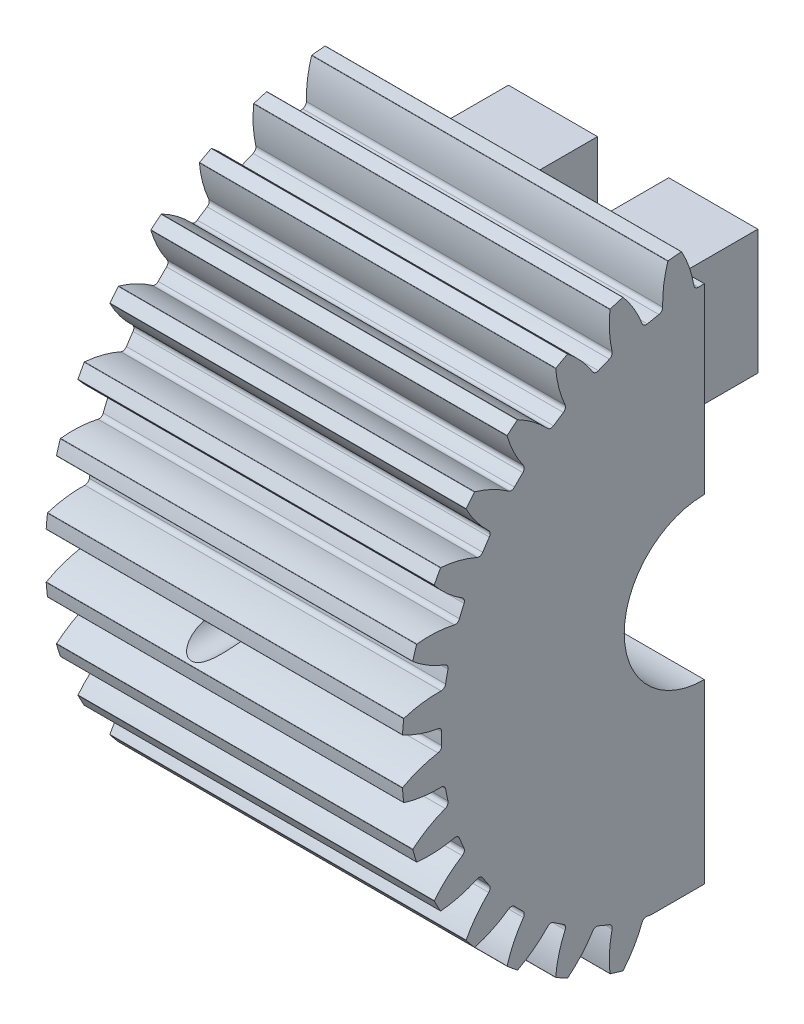
SolidWorks part; units mm, degrees
ref_plane "Plane1" through (0, 0, 0) normal (0, 0, 1) x (1, 0, 0)
ref_plane "Plane2" through (0, 0, 0) normal (0, 1, 0) x (1, 0, 0)
ref_plane "Plane3" through (0, 0, 0) normal (1, 0, 0) x (0, 0, -1)
other "Configuration Table"
sketch "HoldingSke" plane through (0, 0, 0) normal (0, 1, 0) x (1, 0, 0)
  line L0 (0, 0) -> (1.6961, -1.0598)
  line L1 (-15, 0) -> (100, 0) construction
  line L2 (0, 0) -> (-2.1039, 2.3779)
  line L3 (0, 0) -> (-11.863, 4.5341)
  line L4 (0, 0) -> (7.3237, 4.5764)
  line L5 (0, 0) -> (-46.8476, -17.4728)
  line L6 (0, 0) -> (-8.2896, -5.593)
  line L7 (-2.1039, 2.3779) -> (8.6586, 51.2059)
  line L8 (-76.2, 54.61) -> (-75.9, 54.61)
  line L9 (-67.7845, 28.3722) -> (-49.3413, 33.142)
  line L10 (-76.2, 71.12) -> (104.1128, 71.12)
  line L11 (0, 0) -> (-10, 0)
  line L12 (-76.2, 101.6) -> (-76.181, 101.6)
  line L13 (24.9733, 27.94) -> (52.9518, 28.4284)
  line L14 (24.9733, 27.94) -> (24.9743, 27.94)
  line L15 (24.9733, 27.94) -> (100.4006, 29.5858)
  line L16 (-63.627, -0.5) -> (-12.827, -0.5)
  circle A0 centre (0, 0) radius 1
  circle A1 centre (0, 0) radius 7.374
  circle A2 centre (0, 0) radius 37.5
  circle A3 centre (0, 0) radius 1
  dimension "MHD" = 14.748
  dimension "Hub_dia" = 75
  dimension "Bore" = 2
  dimension "MBD" = 2
  dimension "Num_teeth" = 32
  dimension "Pitch" = 2
  dimension "Overall_len" = 50
  dimension "Show_teeth" = 32
  dimension "Thickness" = 10
  dimension "OAL" = 50.0001
  dimension "T_dim" = 0.3
  dimension "Ap" = 14.5
  dimension "H" = 19.05
  dimension "Pitch_radius" = 180.3128
  dimension "Width" = 10
  dimension "Backlash" = 0.019
  dimension "Addendum_fac" = 1
  dimension "Dedendum_fac" = 1.25
  dimension "Clearance_fac" = 0.25
  dimension "Dedendum_add" = 0.001
  dimension "Module" = 0.5
sketch "BasProSke" plane through (0, 0, 0) normal (0, 1, 0) x (1, 0, 0)
  line L0 (-10, 0) -> (60, 0) construction
  line L1 (0, 0) -> (0, 8.5)
  line L2 (0, 0) -> (10, 0)
  line L3 (10, 0) -> (10, 8.5)
  line L4 (10, 8.5) -> (0, 8.5)
  dimension "Thickness" = 10
  dimension "Diameter" = 17
revolve "Base-Revolve" add sketch "BasProSke" angle 360 about L0
sketch "TooCutSke" plane through (0, 0, 0) normal (1, 0, 0) x (0, 0, -1)
  line L1 (0, 0) -> (0, 107) construction
  line L2 (0, 0) -> (-0.4258, 7.9887) construction
  line L3 (0, 0) -> (-1.5667, 15.9069) construction
  line L4 (-0.4258, 7.9887) -> (-0.7833, 7.9534) construction
  arc A0 (0.277, 7.3688) -> (-0.277, 7.3688) centre (0, 0) ccw
  arc A1 (0.6561, 8.5001) -> (-0.6561, 8.5001) centre (0, 0) ccw
  circle A2 centre (0, 0) radius 8 construction
  circle A3 centre (0, 0) radius 7.7452 construction
  arc A4 (-0.277, 7.3688) -> (-0.6561, 8.5001) centre (-3.4475, 6.9356) ccw
  arc A5 (0.6561, 8.5001) -> (0.277, 7.3688) centre (3.4475, 6.9356) ccw
  dimension "Root_dia" = 14.748
  dimension "Overcut_dia" = 17.0508
  dimension "Pitch_dia" = 16
  dimension "Base_dia" = 15.4904
  dimension "Flank_rad" = 3.2
  dimension "Half_ang" = 5.625
  dimension "Half_CT" = 0.3593
extrude "ToothCut" cut sketch "TooCutSke" along normal through all
fillet "Breaks" radius 0.01 2 edges at (5, 8.4757, -0.6425) (5, 8.4757, 0.6425)
fillet "RootFillets" radius 0.126 2 edges at (5, 7.3688, -0.277) (5, 7.3688, 0.277)
pattern_circular "TeethCuts" count 32 over 360 about axis through (0, 0, 0) along (1, 0, 0) of "ToothCut", "RootFillets", "Breaks"
sketch "HubNeaOneSke" plane through (0, 0, 0) normal (-1, 0, 0) x (0, 0, 1)
  circle A0 centre (0, 0) radius 7.374
  dimension "Diameter" = 14.748
extrude "HubNearOne" [suppressed] add sketch "HubNeaOneSke" along normal blind 40.0001
sketch "HubNeaBotSke" plane through (0, 0, 0) normal (-1, 0, 0) x (0, 0, 1)
  circle A0 centre (0, 0) radius 7.374
  dimension "Diameter" = 14.748
extrude "HubNearBoth" [suppressed] add sketch "HubNeaBotSke" along normal blind 20
ref_plane "FarPln" through (10, 0, 0) normal (1, 0, 0) x (0, 0, -1)
sketch "HubFarSke" plane through (10, 0, 0) normal (1, 0, 0) x (0, 0, -1)
  circle A0 centre (0, 0) radius 7.374
  dimension "Diameter" = 14.748
extrude "HubFar" [suppressed] add sketch "HubFarSke" along normal blind 20
sketch "BorSke" plane through (0, 0, 0) normal (1, 0, 0) x (0, 0, -1)
  circle A0 centre (0, 0) radius 1
  dimension "Diameter" = 2
extrude "Bore" cut sketch "BorSke" along normal mid plane 100.0001
sketch "KeySke" plane through (0, 0, 0) normal (1, 0, 0) x (0, 0, -1)
  line L0 (-0.4, 0) -> (-0.4, 1.3)
  line L1 (-0.4, 1.3) -> (0.4, 1.3)
  line L2 (0.4, 1.3) -> (0.4, 0)
  line L3 (0, 0) -> (0, 34) construction
  line L4 (-0.4, 0) -> (0.4, 0)
  dimension "Offset" = 1.3
  dimension "Width" = 0.8
extrude "Keyway" [suppressed] cut sketch "KeySke" along normal mid plane 100.0001
pattern_circular "Keyway2" [suppressed] count 2 every 90 about axis through (-10, 0, 0) along (1, 0, 0)
sketch "Sketch2" plane through (0, 0, 0) normal (-1, 0, 0) x (0, 0, 1)
  line L1 (-1.5, 0) -> (1.5, 0)
  line L2 (-1.5, 0) -> (-1.5, -10)
  line L3 (-1.5, -10) -> (1.5, -10)
  line L4 (1.5, 0) -> (1.5, -10)
  circle A0 centre (0, 0) radius 1 construction
  dimension "D3" = 1.5
  dimension "D1" = 10
  dimension "D2" = 3
  dimension "D4" = 0
extrude "Cut-Extrude2" cut sketch "Sketch2" against normal through all
sketch "Sketch3" plane through (0, 0, -1.5) normal (0, 0, 1) x (1, 0, 0)
  line L0 (0, 0.1666) -> (0, -0.1666) construction
  circle A0 centre (4, 0) radius 0.6
  dimension "D1" = 4
extrude "Cut-Extrude3" cut sketch "Sketch3" against normal through all both and the other way through all
sketch "Sketch4" plane through (0, 0, 0) normal (-1, 0, 0) x (0, 0, 1)
  circle A0 centre (0, 0) radius 1.5
  dimension "D1" = 3
extrude "Cut-Extrude4" cut sketch "Sketch4" against normal blind 6.5
sketch "Sketch7" plane through (0, 0, 0) normal (0, 0, 1) x (1, 0, 0)
  line L0 (4, 0) -> (4, 2.75)
  line L1 (4, 0) -> (4, -2.75)
  arc A0 (4, 2.75) -> (4, -2.75) centre (4, 0) ccw
  dimension "D1" = 2.75
  dimension "D2" = 2.75
revolve "Cut-Revolve1" cut sketch "Sketch7" angle 360 about L0
sketch "Sketch8" plane through (0, 0, 0) normal (0, 0, 1) x (1, 0, 0)
  line L0 (0, 0.1666) -> (0, -0.1666) construction
  line L1 (-0.5, 9) -> (10.5, 9)
  line L2 (-0.5, 9) -> (-0.5, -9)
  line L3 (-0.5, -9) -> (10.5, -9)
  line L4 (10.5, 9) -> (10.5, -9)
  point P7 (0, 0)
  dimension "D1" = 18
  dimension "D2" = 11
  dimension "D3" = 9
  dimension "D4" = 10.5
extrude "Cut-Extrude5" cut sketch "Sketch8" against normal blind 10
sketch "Sketch9" plane through (0, 0, 0) normal (0, 0, -1) x (-1, 0, 0)
  line L1 (-4, 6.45) -> (-1.5, 6.45)
  line L2 (-4, 6.45) -> (-4, 2.95)
  line L3 (-4, 2.95) -> (-1.5, 2.95)
  line L4 (-1.5, 6.45) -> (-1.5, 2.95)
  line L5 (-4, 6.45) -> (-1.5, 2.95) construction
  line L6 (-4, 2.95) -> (-1.5, 6.45) construction
  line L7 (-8.5, 6.45) -> (-6, 6.45)
  line L8 (-8.5, 6.45) -> (-8.5, 2.95)
  line L9 (-8.5, 2.95) -> (-6, 2.95)
  line L10 (-6, 6.45) -> (-6, 2.95)
  line L11 (-8.5, 6.45) -> (-6, 2.95) construction
  line L12 (-8.5, 2.95) -> (-6, 6.45) construction
  point P0 (-2.75, 4.7)
  point P5 (-7.25, 4.7)
  dimension "D1" = 3.5
  dimension "D2" = 3.5
  dimension "D3" = 2.5
  dimension "D4" = 2.5
  dimension "D5" = 4.7
  dimension "D6" = 4.7
  dimension "D7" = 8.5
  dimension "D8" = 4
extrude "Boss-Extrude1" add sketch "Sketch9" along normal blind 3
sketch "Sketch12" plane through (0, 0, 1.5) normal (0, 0, -1) x (-1, 0, 0)
  line L0 (-10, -7.2198) -> (0, -7.2198) construction
  line L1 (-10, 0) -> (-6.75, 0)
  line L2 (-10, 0) -> (-10, -7.2198)
  line L3 (-10, -7.2198) -> (-6.75, -7.2198)
  line L4 (-6.75, 0) -> (-6.75, -7.2198)
  dimension "D1" = 3.25
extrude "Boss-Extrude3" add sketch "Sketch12" along normal blind 1.5
sketch "Sketch1" plane through (10, 0, 0) normal (1, 0, 0) x (0, 0, -1)
  circle A0 centre (0, 0) radius 2.25
  dimension "D1" = 4.5
extrude "Cut-Extrude6" cut sketch "Sketch1" against normal blind 3.25
equation "' \"Module@HoldingSke\" = 6.35"
equation "' \"Num_teeth@HoldingSke\" = 12"
equation "' \"Ap@HoldingSke\" =  20"
equation "' \"Ap@HoldingSke\" = 20"
equation "' \"Width@HoldingSke\" = 0.5 * 25.4"
equation "' \"Hub_dia@HoldingSke\"= 1 * 25.4"
equation "' \"Hub_dia@HoldingSke\" = 1 * 25.4"
equation "' \"Overall_len@HoldingSke\" = 1.0 * 25.4"
equation "' \"Bore@HoldingSke\" = 0.75 * 25.4"
equation "' \"T_dim@HoldingSke\" = 0.1 * 25.4"
equation "' \"Width@KeySke\" = 0.25 * 25.4"
equation "' \"Show_teeth@HoldingSke\" = 13"
equation "' \"Backlash@HoldingSke\" = 0.009 * 25.4"
equation "' \"Addendum_fac@HoldingSke\" = 1.0"
equation "' \"Dedendum_fac@HoldingSke\" = 1.25"
equation "' \"Dedendum_add@HoldingSke\" = 0.00005 * 25.4"
equation "' \"Clearance_fac@HoldingSke\" = 0.25"
equation "\"Pitch@HoldingSke\" = 1 / \"Module@HoldingSke\""
equation "\"Overcut_dia@TooCutSke\" = (\"Num_teeth@HoldingSke\" + 2 * \"Addendum_fac@HoldingSke\") / \"Pitch@HoldingSke\" + 0.002 * 25.4"
equation "\"Pitch_dia@TooCutSke\" = \"Num_teeth@HoldingSke\" / \"Pitch@HoldingSke\""
equation "\"Base_dia@TooCutSke\" = \"Num_teeth@HoldingSke\" / \"Pitch@HoldingSke\" * cos((\"Ap@HoldingSke\"  * 3.14159265 / 180))"
equation "\"Root_dia@TooCutSke\" = (\"Num_teeth@HoldingSke\" + 2) / \"Pitch@HoldingSke\" - 2 * (\"Addendum_fac@HoldingSke\" + \"Dedendum_fac@HoldingSke\") / \"Pitch@HoldingSke\" - \"Dedendum_add@HoldingSke\" * 2"
equation "\"Half_ang@TooCutSke\" = 180 / \"Num_teeth@HoldingSke\""
equation "\"Half_CT@TooCutSke\" = \"Num_teeth@HoldingSke\" / \"Pitch@HoldingSke\" * sin((3.14159265 / 2 / \"Num_teeth@HoldingSke\")) / 2 - 7 * \"Backlash@HoldingSke\" / 4"
equation "\"Flank_rad@TooCutSke\" = \"Num_teeth@HoldingSke\" / \"Pitch@HoldingSke\" / 5"
equation "\"Radius@RootFillets\" = \"Clearance_fac@HoldingSke\" / \"Pitch@HoldingSke\" + \"Dedendum_add@HoldingSke\""
equation "\"Break_rad@Breaks\" = 0.02 / \"Pitch@HoldingSke\""
equation "\"Thickness@HoldingSke\" = \"Width@HoldingSke\""
equation "\"OAL@HoldingSke\" = \"Thickness@HoldingSke\""
equation "\"MHD@HoldingSke\" = (\"Num_teeth@HoldingSke\" + 2) / \"Pitch@HoldingSke\" - 2 * (\"Addendum_fac@HoldingSke\" + \"Dedendum_fac@HoldingSke\")  / \"Pitch@HoldingSke\" - \"Dedendum_add@HoldingSke\" * 2"
equation "\"MBD@HoldingSke\" = (\"Num_teeth@HoldingSke\" + 2) / \"Pitch@HoldingSke\" - 2 * (\"Addendum_fac@HoldingSke\" + \"Dedendum_fac@HoldingSke\")  / \"Pitch@HoldingSke\" - \"Dedendum_add@HoldingSke\" * 2 - 0.002 * 25.4"
equation "\"MHD@HoldingSke\" = ((sgn( \"MHD@HoldingSke\" - \"Hub_dia@HoldingSke\" )-1)*( \"MHD@HoldingSke\" - \"Hub_dia@HoldingSke\" ))/-2+ \"Hub_dia@HoldingSke\""
equation "\"MBD@HoldingSke\" = ((sgn( \"MBD@HoldingSke\" - \"Bore@HoldingSke\" )-1)*( \"MBD@HoldingSke\" - \"Bore@HoldingSke\" ))/-2+ \"Bore@HoldingSke\""
equation "\"OAL@HoldingSke\" = ((sgn( \"OAL@HoldingSke\" - \"Overall_len@HoldingSke\" )+1)*( \"OAL@HoldingSke\" - \"Overall_len@HoldingSke\" ))/2 + \"Overall_len@HoldingSke\" + 0.000002 * 25.4"
equation "\"Num_teeth@TeethCuts\" = int( \"Show_teeth@HoldingSke\" ) + 1"
equation "\"Num_teeth@TeethCuts\" = ((sgn( \"Num_teeth@TeethCuts\" - \"Num_teeth@HoldingSke\" )-1)*( \"Num_teeth@TeethCuts\" - \"Num_teeth@HoldingSke\" ))/-2+ \"Num_teeth@HoldingSke\""
equation "\"Num_teeth@TeethCuts\" = ((sgn( \"Num_teeth@TeethCuts\" - 2.0)+1)*( \"Num_teeth@TeethCuts\" - 2.0))/2 +2.0"
equation "\"Angle@TeethCuts\" = 360.0 / \"Num_teeth@HoldingSke\""
equation "\"Diameter@BasProSke\" = (\"Num_teeth@HoldingSke\" + 2 * \"Addendum_fac@HoldingSke\") / \"Pitch@HoldingSke\""
equation "\"Thickness@BasProSke\"  = \"Thickness@HoldingSke\""
equation "' \"Fillet_rad@BasProSke\" =  \"Thickness@HoldingSke\" * 0.05"
equation "' \"Fillet_rad@BasProSke\" = \"Thickness@HoldingSke\" * 0.05"
equation "\"MHD@HoldingSke\" = ((sgn( \"MHD@HoldingSke\" - \"Root_dia@TooCutSke\" )-1)*( \"MHD@HoldingSke\" - \"Root_dia@TooCutSke\" ))/-2+ \"Root_dia@TooCutSke\""
equation "\"Diameter@HubNeaOneSke\" = \"MHD@HoldingSke\""
equation "\"Length@HubNearOne\" = \"OAL@HoldingSke\" - \"Thickness@BasProSke\""
equation "\"Diameter@HubNeaBotSke\" = \"MHD@HoldingSke\""
equation "\"Length@HubNearBoth\" = ( \"OAL@HoldingSke\" - \"Thickness@BasProSke\" ) / 2.0"
equation "\"Thickness@FarPln\" = \"Thickness@BasProSke\""
equation "\"Diameter@HubFarSke\" = \"MHD@HoldingSke\""
equation "\"Length@HubFar\" = ( \"OAL@HoldingSke\" - \"Thickness@BasProSke\" ) / 2.0"
equation "\"Diameter@BorSke\" = \"MBD@HoldingSke\""
equation "\"D1@Bore\" = \"OAL@HoldingSke\" * 2.0"
equation "\"D1@Keyway\" = \"OAL@HoldingSke\" * 2.0"
equation "\"Offset@KeySke\" = \"T_dim@HoldingSke\" + \"MBD@HoldingSke\" / 2.0"
